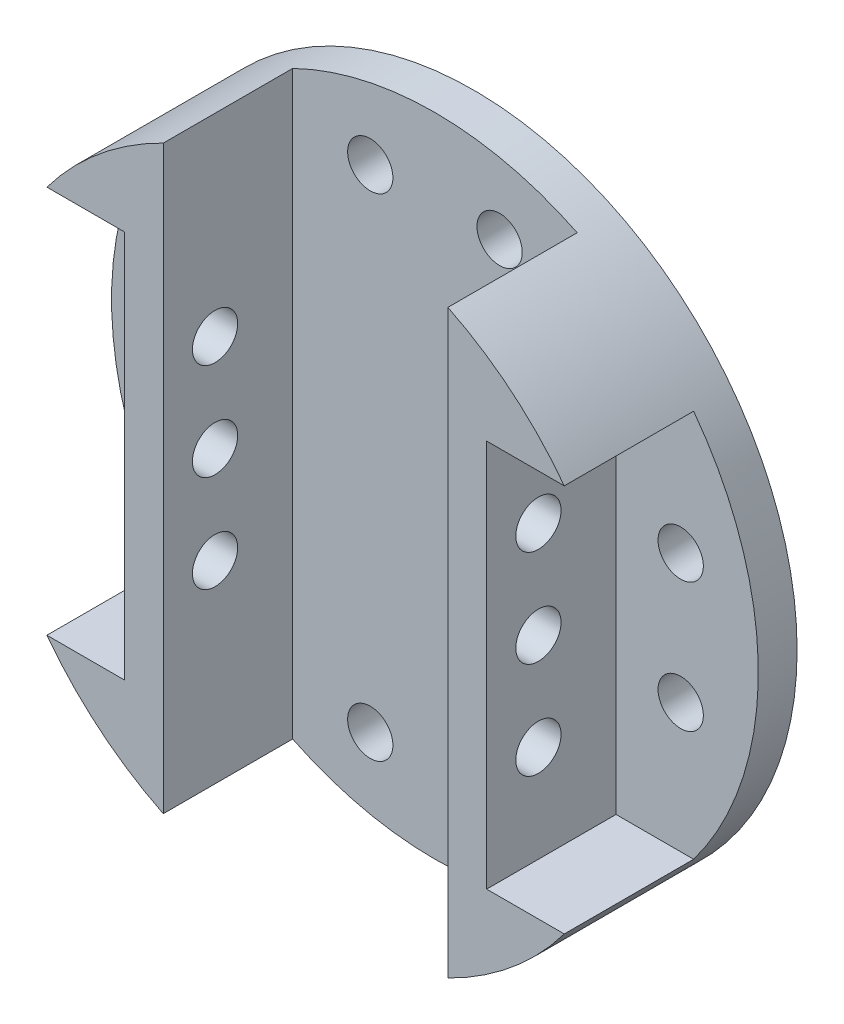
SolidWorks part; units mm, degrees
ref_plane "Front Plane" through (0, 0, 0) normal (0, 0, 1) x (1, 0, 0)
ref_plane "Top Plane" through (0, 0, 0) normal (0, 1, 0) x (1, 0, 0)
ref_plane "Right Plane" through (0, 0, 0) normal (1, 0, 0) x (0, 0, -1)
sketch "Sketch1" plane through (0, 0, 0) normal (0, 0, 1) x (1, 0, 0)
  circle A0 centre (0, 0) radius 25
  dimension "D1" = 50
extrude "Boss-Extrude1" add sketch "Sketch1" along normal blind 13
sketch "Sketch3" plane through (0, 0, 13) normal (0, 0, 1) x (1, 0, 0)
  line L0 (-25, 0) -> (25, 0) construction
  line L1 (-11, 25) -> (11, 25)
  line L2 (-11, 25) -> (-11, -25)
  line L3 (-11, -25) -> (11, -25)
  line L4 (11, 25) -> (11, -25)
  line L5 (-11, 25) -> (11, -25) construction
  line L6 (-11, -25) -> (11, 25) construction
  line L7 (36, 15) -> (14, 15)
  line L8 (36, 15) -> (36, -15)
  line L9 (36, -15) -> (14, -15)
  line L10 (14, 15) -> (14, -15)
  line L11 (36, 15) -> (14, -15) construction
  line L12 (36, -15) -> (14, 15) construction
  line L13 (-36, 15) -> (-14, 15)
  line L14 (-36, 15) -> (-36, -15)
  line L15 (-36, -15) -> (-14, -15)
  line L16 (-14, 15) -> (-14, -15)
  line L17 (-36, 15) -> (-14, -15) construction
  line L18 (-36, -15) -> (-14, 15) construction
  circle A0 centre (0, 0) radius 25 construction
  point P0 (0, 0)
  point P6 (25, 0)
  point P13 (-25, 0)
  point P20 (0, 0)
  dimension "D1" = 22
  dimension "D2" = 3
  dimension "D3" = 3
  dimension "D4" = 30
extrude "Cut-Extrude1" cut sketch "Sketch3" against normal blind 10
sketch "Sketch4" plane through (0, 0, 0) normal (1, 0, 0) x (0, 0, -1)
  line L0 (-3, 0) -> (-9, 0) construction
  line L1 (-3, 15) -> (-3, -15) construction
  line L2 (-9, 7.5) -> (-9, -7.5) construction
  circle A0 centre (-9, 7.5) radius 1.75
  circle A1 centre (-9, 0) radius 1.75
  circle A2 centre (-9, -7.5) radius 1.75
  dimension "D3" = 3.5
  dimension "D1" = 6
  dimension "D2" = 15
extrude "Cut-Extrude2" cut sketch "Sketch4" against normal through all both and the other way through all
sketch "Sketch5" plane through (0, 0, 3) normal (0, 0, 1) x (1, 0, 0)
  line L0 (0, 0) -> (-19, 0) construction
  line L1 (-19, 0) -> (-19, 5) construction
  line L3 (0, 0) -> (0, 19) construction
  line L4 (0, 19) -> (-5, 19) construction
  circle A0 centre (-19, 5) radius 1.75
  circle A1 centre (-5, 19) radius 1.75
  dimension "D2" = 3.5
  dimension "D6" = 3.5
  dimension "D1" = 5
  dimension "D3" = 19
  dimension "D4" = 19
  dimension "D5" = 5
extrude "Cut-Extrude3" cut sketch "Sketch5" against normal through all
mirror "Mirror1" about plane through (0, 0, 0) normal (1, 0, 0) of "Cut-Extrude3" second plane through (0, 0, 0) second plane normal (0, 1, 0)
